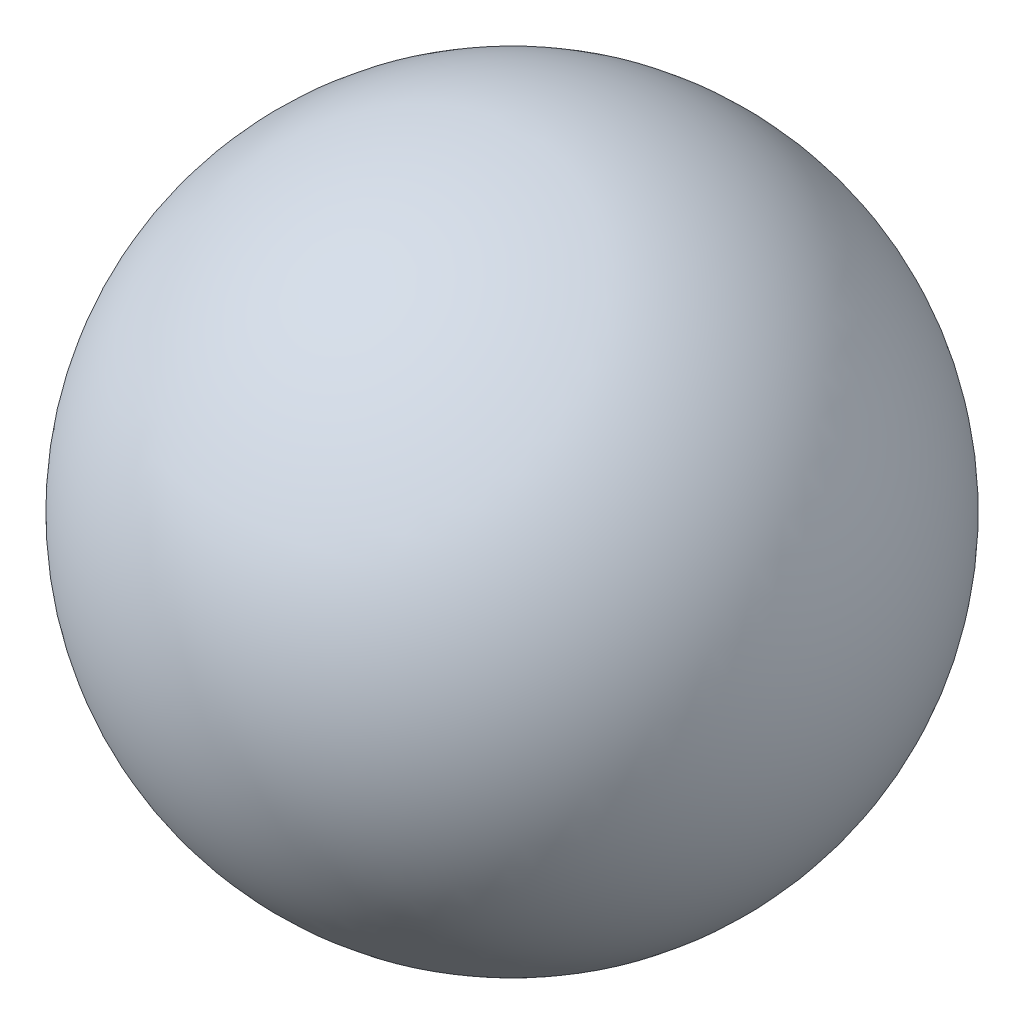
SolidWorks part; units mm, degrees
ref_plane "Front Plane" through (0, 0, 0) normal (0, 0, 1) x (1, 0, 0)
ref_plane "Top Plane" through (0, 0, 0) normal (0, 1, 0) x (1, 0, 0)
ref_plane "Right Plane" through (0, 0, 0) normal (1, 0, 0) x (0, 0, -1)
other "Sphere"
sketch "Sketch1" plane through (0, 0, 0) normal (0, 0, 1) x (1, 0, 0)
  line L2 (2, 29.6827) -> (2, -29.6827) construction
  line L3 (0, 31.75) -> (0, -31.75) construction
  line L6 (0, -31.75) -> (0, -29.6827)
  line L7 (0, -29.6827) -> (2, -29.6827)
  line L8 (0, 31.75) -> (0, 29.6827)
  line L9 (0, 29.6827) -> (2, 29.6827)
  arc A0 (0, -31.75) -> (0, 31.75) centre (0, 0) ccw
  arc A1 (2, -29.6827) -> (2, 29.6827) centre (0, 0) ccw
  dimension "D1" = 63.5
  dimension "D2" = 2
sketch "Sketch2" plane through (0, 0, 0) normal (0, 1, 0) x (1, 0, 0)
  circle A0 centre (0, 0) radius 31.75
  dimension "D1" = 63.5
sketch "Bearing Profile" plane through (0, 0, 0) normal (1, 0, 0) x (0, 0, -1)
  circle A0 centre (0, 0) radius 11.125
  circle A1 centre (0, 0) radius 13.125
  dimension "D1" = 22.25
  dimension "D2" = 2
sketch "10degree" plane through (0, 0, 0) normal (1, 0, 0) x (0, 0, -1)
  line L0 (29.5, 0) -> (31.75, 0)
  line L1 (29.0518, -5.1226) -> (31.2676, -5.5133)
  line L2 (27.7209, -10.0896) -> (29.8352, -10.8591)
  line L3 (25.5477, -14.75) -> (27.4963, -15.875)
  line L4 (22.5983, -18.9622) -> (24.3219, -20.4085)
  line L5 (18.9622, -22.5983) -> (20.4085, -24.3219)
  line L6 (14.75, -25.5477) -> (15.875, -27.4963)
  line L7 (10.0896, -27.7209) -> (10.8591, -29.8352)
  line L8 (5.1226, -29.0518) -> (5.5133, -31.2676)
  line L9 (0, -29.5) -> (0, -31.75)
  line L10 (-5.1226, -29.0518) -> (-5.5133, -31.2676)
  line L11 (-10.0896, -27.7209) -> (-10.8591, -29.8352)
  line L12 (-14.75, -25.5477) -> (-15.875, -27.4963)
  line L13 (-18.9622, -22.5983) -> (-20.4085, -24.3219)
  line L14 (-22.5983, -18.9622) -> (-24.3219, -20.4085)
  line L15 (-25.5477, -14.75) -> (-27.4963, -15.875)
  line L16 (-27.7209, -10.0896) -> (-29.8352, -10.8591)
  line L17 (-29.0518, -5.1226) -> (-31.2676, -5.5133)
  line L18 (-29.5, 0) -> (-31.75, 0)
  line L19 (-29.0518, 5.1226) -> (-31.2676, 5.5133)
  line L20 (-27.7209, 10.0896) -> (-29.8352, 10.8591)
  line L21 (-25.5477, 14.75) -> (-27.4963, 15.875)
  line L22 (-22.5983, 18.9622) -> (-24.3219, 20.4085)
  line L23 (-18.9622, 22.5983) -> (-20.4085, 24.3219)
  line L24 (-14.75, 25.5477) -> (-15.875, 27.4963)
  line L25 (-10.0896, 27.7209) -> (-10.8591, 29.8352)
  line L26 (-5.1226, 29.0518) -> (-5.5133, 31.2676)
  line L27 (0, 29.5) -> (0, 31.75)
  line L28 (5.1226, 29.0518) -> (5.5133, 31.2676)
  line L29 (10.0896, 27.7209) -> (10.8591, 29.8352)
  line L30 (14.75, 25.5477) -> (15.875, 27.4963)
  line L31 (18.9622, 22.5983) -> (20.4085, 24.3219)
  line L32 (22.5983, 18.9622) -> (24.3219, 20.4085)
  line L33 (25.5477, 14.75) -> (27.4963, 15.875)
  line L34 (27.7209, 10.0896) -> (29.8352, 10.8591)
  line L35 (29.0518, 5.1226) -> (31.2676, 5.5133)
  circle A0 centre (0, 0) radius 31.75
  circle A1 centre (0, 0) radius 31.75
  circle A2 centre (0, 0) radius 31.75
  circle A3 centre (0, 0) radius 31.75
  circle A4 centre (0, 0) radius 31.75
  circle A5 centre (0, 0) radius 31.75
  circle A6 centre (0, 0) radius 31.75
  circle A7 centre (0, 0) radius 31.75
  circle A8 centre (0, 0) radius 31.75
  circle A9 centre (0, 0) radius 31.75
  circle A10 centre (0, 0) radius 31.75
  circle A11 centre (0, 0) radius 31.75
  circle A12 centre (0, 0) radius 31.75
  circle A13 centre (0, 0) radius 31.75
  circle A14 centre (0, 0) radius 31.75
  circle A15 centre (0, 0) radius 31.75
  circle A16 centre (0, 0) radius 31.75
  circle A17 centre (0, 0) radius 31.75
  circle A18 centre (0, 0) radius 31.75
  circle A19 centre (0, 0) radius 31.75
  circle A20 centre (0, 0) radius 31.75
  circle A21 centre (0, 0) radius 31.75
  circle A22 centre (0, 0) radius 31.75
  circle A23 centre (0, 0) radius 31.75
  circle A24 centre (0, 0) radius 31.75
  circle A25 centre (0, 0) radius 31.75
  circle A26 centre (0, 0) radius 31.75
  circle A27 centre (0, 0) radius 31.75
  circle A28 centre (0, 0) radius 31.75
  circle A29 centre (0, 0) radius 31.75
  circle A30 centre (0, 0) radius 31.75
  circle A31 centre (0, 0) radius 31.75
  circle A32 centre (0, 0) radius 31.75
  circle A33 centre (0, 0) radius 31.75
  circle A34 centre (0, 0) radius 31.75
  circle A35 centre (0, 0) radius 31.75
  circle A36 centre (0, 0) radius 29.5 construction
  point P76 (0, 0)
  dimension "D1" = 63.5
  dimension "D3" = 2.25
  dimension "D2" = 36
revolve "Revolve1" add sketch "Sketch1" angle 360 about L8
